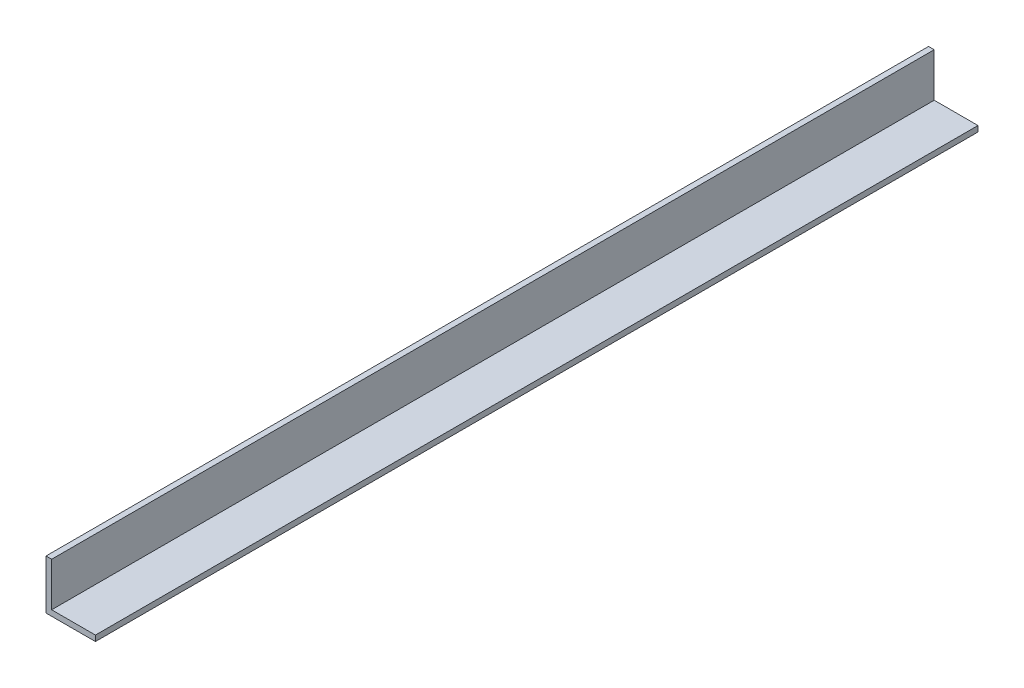
SolidWorks part; units mm, degrees
ref_plane "Спереди" through (0, 0, 0) normal (0, 0, 1) x (1, 0, 0)
ref_plane "Сверху" through (0, 0, 0) normal (0, 1, 0) x (1, 0, 0)
ref_plane "Справа" through (0, 0, 0) normal (1, 0, 0) x (0, 0, -1)
sketch "Эскиз1" plane through (0, 0, 0) normal (0, 0, 1) x (1, 0, 0)
  line L0 (-35, 70) -> (-35, 0)
  line L1 (-35, 0) -> (35, 0)
  line L2 (35, 0) -> (35, 8)
  line L3 (35, 8) -> (-27, 8)
  line L4 (-27, 8) -> (-27, 70)
  line L5 (-27, 70) -> (-35, 70)
  dimension "D1" = 70
  dimension "D2" = 70
  dimension "D3" = 8
extrude "Бобышка-Вытянуть1" add sketch "Эскиз1" along normal blind 1250
